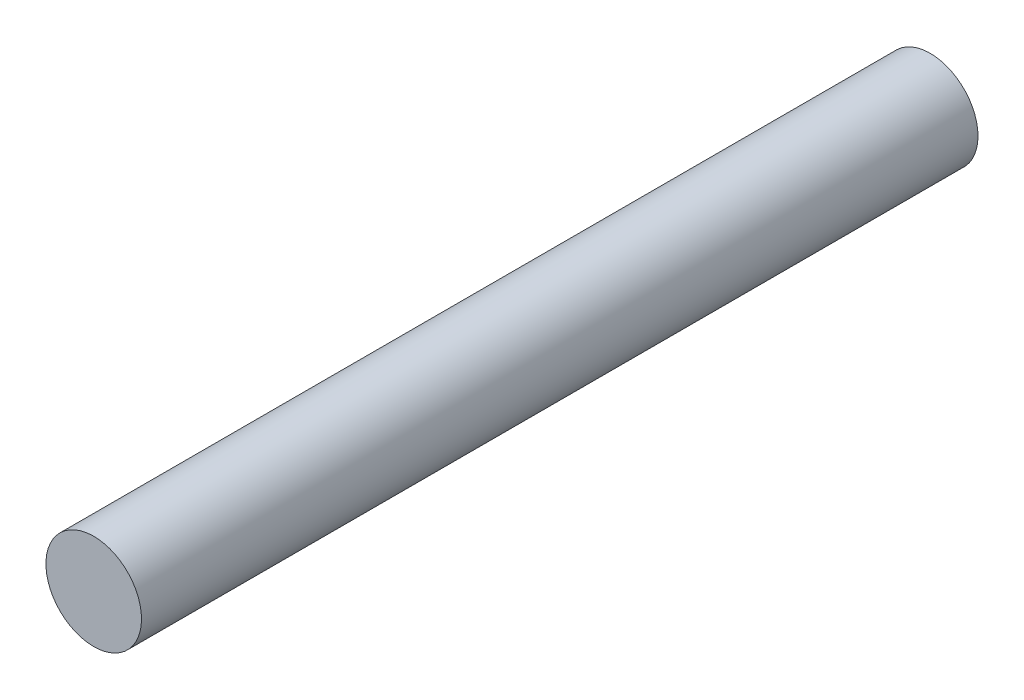
SolidWorks part; units mm, degrees
ref_plane "Front Plane" through (0, 0, 0) normal (0, 0, 1) x (1, 0, 0)
ref_plane "Top Plane" through (0, 0, 0) normal (0, 1, 0) x (1, 0, 0)
ref_plane "Right Plane" through (0, 0, 0) normal (1, 0, 0) x (0, 0, -1)
sketch "Sketch1" plane through (0, 0, 0) normal (0, 0, 1) x (1, 0, 0)
  circle A0 centre (0, 0) radius 4
extrude "Boss-Extrude1" add sketch "Sketch1" along normal blind 70
sketch "Sketch2" plane through (0, 0, 0) normal (0, 0, -1) x (-1, 0, 0)
  circle A0 centre (0, 0) radius 2.5
  dimension "D1" = 5
extrude "Cut-Extrude1" cut sketch "Sketch2" against normal blind 6
